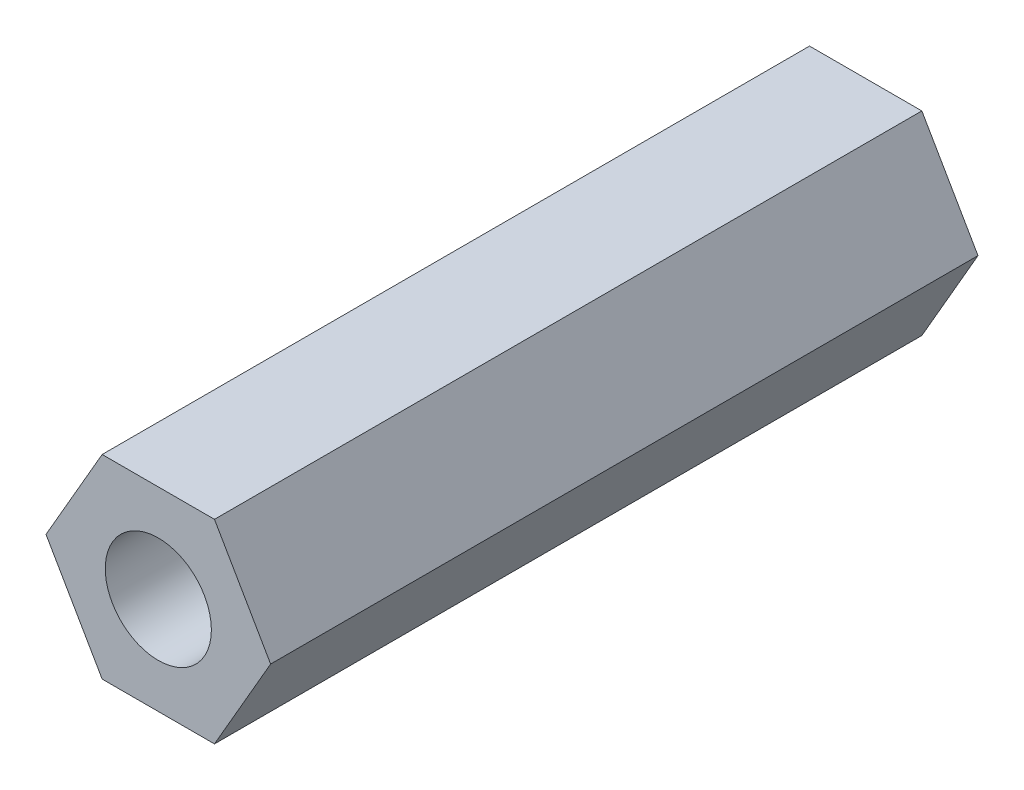
SolidWorks part; units mm, degrees
ref_plane "Front Plane" through (0, 0, 0) normal (0, 0, 1) x (1, 0, 0)
ref_plane "Top Plane" through (0, 0, 0) normal (0, 1, 0) x (1, 0, 0)
ref_plane "Right Plane" through (0, 0, 0) normal (1, 0, 0) x (0, 0, -1)
sketch "Sketch1" plane through (0, 0, 0) normal (0, 0, 1) x (1, 0, 0)
  line L1 (3.1754, 0) -> (1.5877, 2.75)
  line L2 (1.5877, 2.75) -> (-1.5877, 2.75)
  line L3 (-1.5877, 2.75) -> (-3.1754, 0)
  line L4 (-3.1754, 0) -> (-1.5877, -2.75)
  line L5 (-1.5877, -2.75) -> (1.5877, -2.75)
  line L6 (1.5877, -2.75) -> (3.1754, 0)
  circle A0 centre (0, 0) radius 1.5
  circle A1 centre (0, 0) radius 2.75 construction
  dimension "D2" = 3
  dimension "D1" = 5.5
extrude "Boss-Extrude1" add sketch "Sketch1" along normal blind 20
